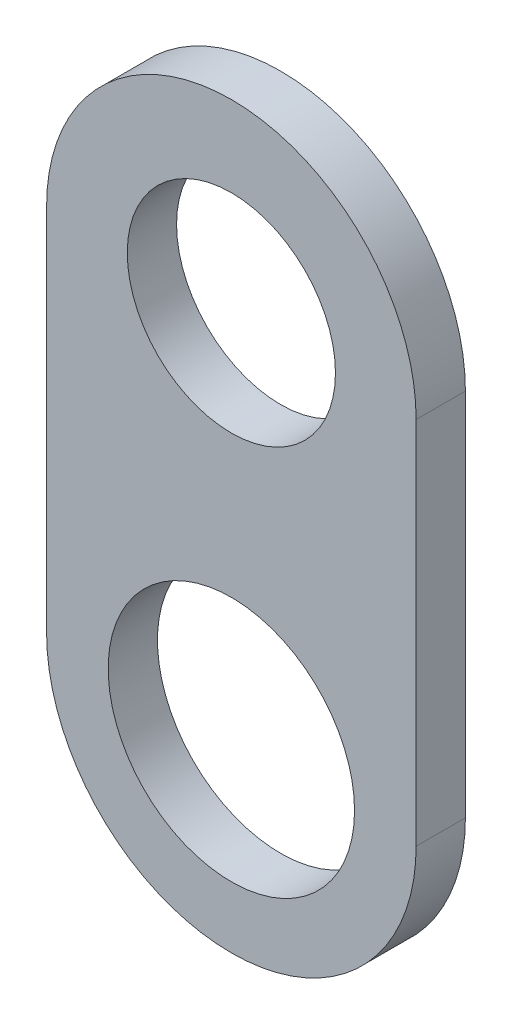
SolidWorks part; units mm, degrees
material "6061-T6 (SS)"
ref_plane "Front Plane" through (0, 0, 0) normal (0, 0, 1) x (1, 0, 0)
ref_plane "Top Plane" through (0, 0, 0) normal (0, 1, 0) x (1, 0, 0)
ref_plane "Right Plane" through (0, 0, 0) normal (1, 0, 0) x (0, 0, -1)
sketch "Sketch1" plane through (0, 0, 0) normal (0, 0, 1) x (1, 0, 0)
  line L0 (0, -38.1) -> (0, 0) construction
  line L1 (-19.05, -38.1) -> (-19.05, 0)
  line L2 (19.05, -38.1) -> (19.05, 0)
  circle A0 centre (0, 0) radius 10.7315
  circle A1 centre (0, -38.1) radius 12.7
  arc A2 (-19.05, -38.1) -> (19.05, -38.1) centre (0, -38.1) ccw
  arc A3 (19.05, 0) -> (-19.05, 0) centre (0, 0) ccw
  point P5 (0, -19.05)
  dimension "D1" = 21.463
  dimension "D2" = 25.4
  dimension "D3" = 6.35
  dimension "D4" = 38.1
extrude "Boss-Extrude1" add sketch "Sketch1" along normal blind 5.08
equation "\"F\"= 500"
equation "\"StressY\"= 40000"
equation "\"SF\"= 4"
equation "\"A\"= ( \"F\" * \"SF\" ) / ( \"StressY\" )"
equation "\"w\"= \"A\" / 0.2"
equation "\"th\"= \"A\" / 0.25"
equation "\"D3@Sketch1\"=\"w\""
equation "\"D1@Boss-Extrude1\"=\"th\""
